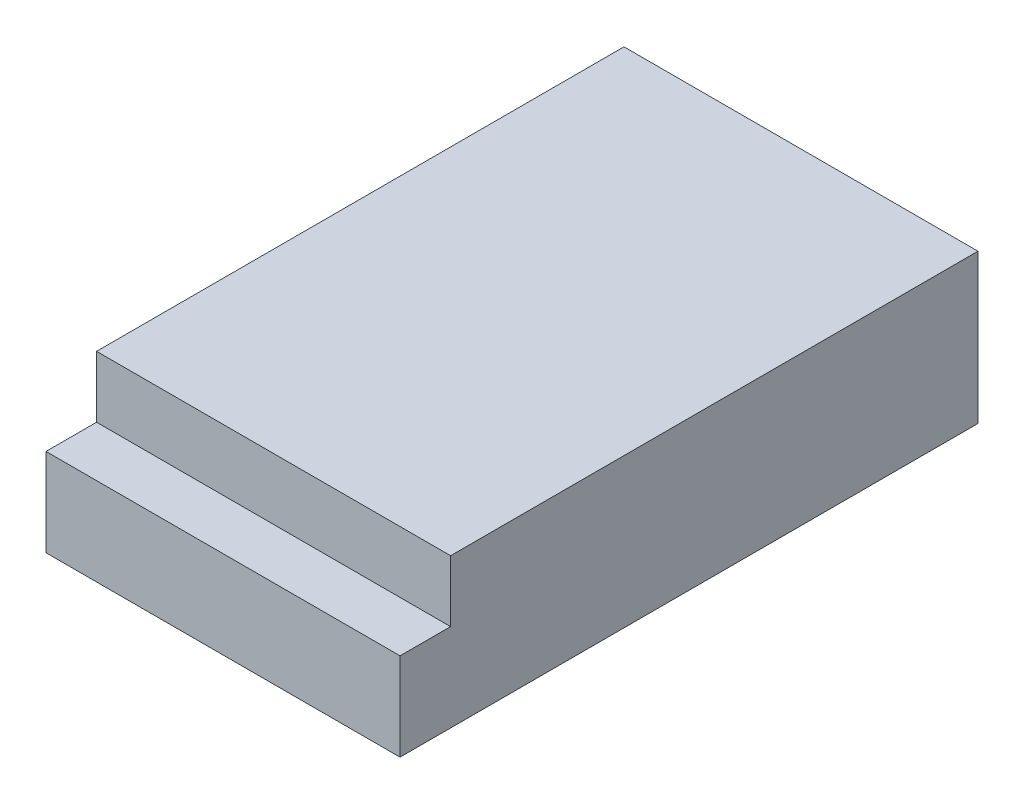
SolidWorks part; units mm, degrees
ref_plane "Plano frontal" through (0, 0, 0) normal (0, 0, 1) x (1, 0, 0)
ref_plane "Plano superior" through (0, 0, 0) normal (0, 1, 0) x (1, 0, 0)
ref_plane "Plano direito" through (0, 0, 0) normal (1, 0, 0) x (0, 0, -1)
sketch "Esboço1" plane through (0, 0, 0) normal (0, 1, 0) x (1, 0, 0)
  line L1 (-49, -80) -> (49, -80)
  line L2 (-49, -80) -> (-49, 80)
  line L3 (-49, 80) -> (49, 80)
  line L4 (49, -80) -> (49, 80)
  line L5 (-49, -80) -> (49, 80) construction
  line L6 (-49, 80) -> (49, -80) construction
  point P0 (0, 0)
  dimension "D1" = 98
  dimension "D2" = 160
extrude "Ressalto-extrusão1" add sketch "Esboço1" along normal blind 41.3
sketch "Esboço2" plane through (49, 0, 0) normal (1, 0, 0) x (0, 0, -1)
  line L1 (-80, 41.3) -> (-66, 41.3)
  line L2 (-80, 41.3) -> (-80, 24.3)
  line L3 (-80, 24.3) -> (-66, 24.3)
  line L4 (-66, 41.3) -> (-66, 24.3)
  dimension "D1" = 17
  dimension "D2" = 14
extrude "Corte-extrusão1" cut sketch "Esboço2" against normal through all
